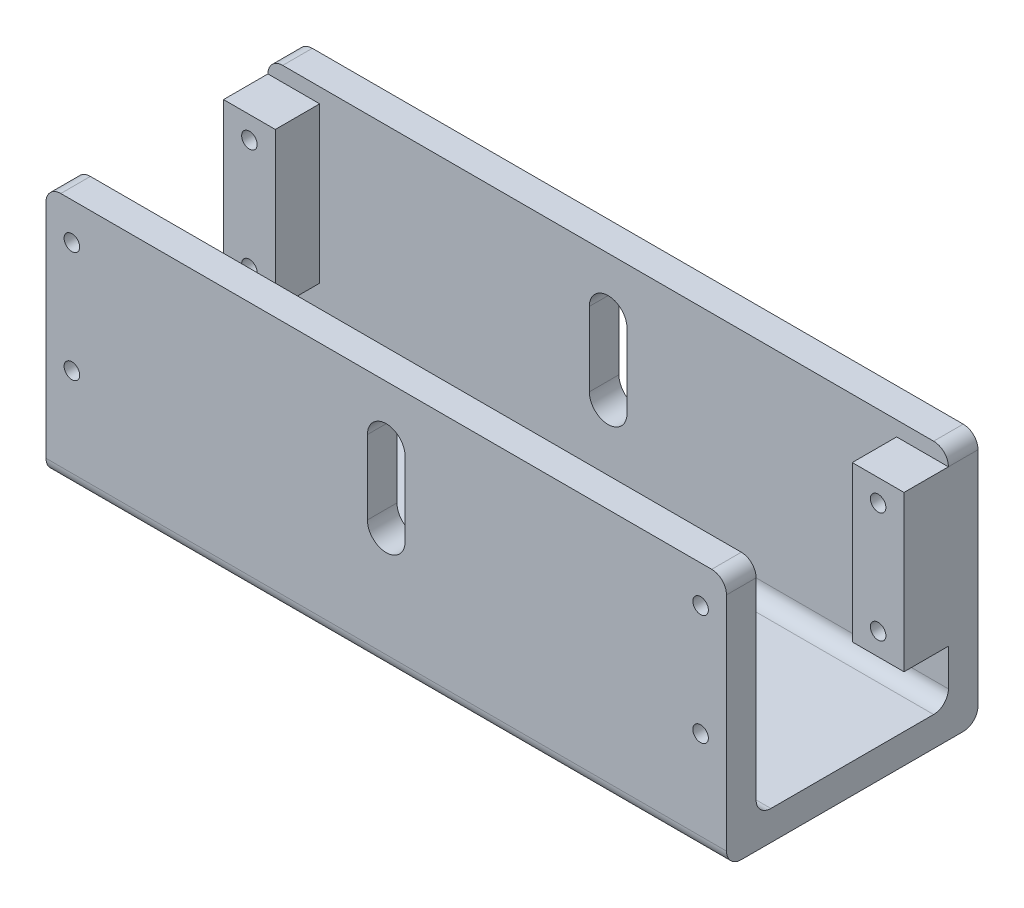
SolidWorks part; units mm, degrees
ref_plane "前视基准面" through (0, 0, 0) normal (0, 0, 1) x (1, 0, 0)
ref_plane "上视基准面" through (0, 0, 0) normal (0, 1, 0) x (1, 0, 0)
ref_plane "右视基准面" through (0, 0, 0) normal (1, 0, 0) x (0, 0, -1)
sketch "草图1" plane through (0, 0, 0) normal (0, 0, 1) x (1, 0, 0)
  line L1 (0, 0) -> (92, 0)
  line L2 (0, 0) -> (0, -30)
  line L3 (0, -30) -> (92, -30)
  line L4 (92, 0) -> (92, -30)
  line L5 (43.45, -17.5) -> (43.45, -7.5)
  line L6 (48.55, -17.5) -> (48.55, -7.5)
  circle A0 centre (3.5, -5) radius 1.05
  circle A1 centre (3.5, -20) radius 1.05
  circle A2 centre (88.5, -5) radius 1.05
  circle A3 centre (88.5, -20) radius 1.05
  arc A7 (43.45, -17.5) -> (48.55, -17.5) centre (46, -17.5) ccw
  arc A8 (48.55, -7.5) -> (43.45, -7.5) centre (46, -7.5) ccw
  point P17 (46.1066, -12.5)
  point P22 (46, 0)
  dimension "D3" = 2
  dimension "D5" = 7.5
  dimension "D6" = 5
  dimension "D1" = 92
  dimension "D2" = 30
  dimension "D7" = 43.45
  dimension "D8" = 5.1
  dimension "D4" = 2
extrude "凸台-拉伸1" add sketch "草图1" along normal blind 4
sketch "草图4" plane through (0, -30, 0) normal (0, -1, 0) x (-1, 0, 0)
  line L1 (0, 0) -> (-92, 0)
  line L2 (0, 0) -> (0, -30)
  line L3 (0, -30) -> (-92, -30)
  line L4 (-92, 0) -> (-92, -30)
  dimension "D1" = 92
  dimension "D2" = 30
extrude "凸台-拉伸4" add sketch "草图4" along normal blind 4
sketch "草图5" plane through (0, 0, 30) normal (0, 0, 1) x (1, 0, 0)
  line L1 (0, -34) -> (92, -34)
  line L2 (0, -34) -> (0, 0)
  line L3 (0, 0) -> (92, 0)
  line L4 (92, -34) -> (92, 0)
  circle A0 centre (3.5, -5) radius 1.05
  circle A1 centre (3.5, -20) radius 1.05
  circle A2 centre (88.5, -20) radius 1.05
  circle A3 centre (88.5, -5) radius 1.05
extrude "凸台-拉伸5" add sketch "草图5" along normal blind 4
fillet "圆角4" radius 2 8 edges at (46, -30, 30) (0, 0, 32) (92, 0, 32) (92, 0, 2) (0, 0, 2) (46, -34, 0) (46, -34, 34) (46, -30, 4)
sketch "草图7" plane through (0, 0, 0) normal (0, 0, -1) x (-1, 0, 0)
  line L0 (-46, -17.5) -> (-46, -7.5) construction
  line L1 (-48.55, -17.5) -> (-48.55, -7.5)
  line L2 (-43.45, -17.5) -> (-43.45, -7.5)
  arc A0 (-48.55, -17.5) -> (-43.45, -17.5) centre (-46, -17.5) ccw
  arc A1 (-43.45, -7.5) -> (-48.55, -7.5) centre (-46, -7.5) ccw
  point P4 (-46, -12.5)
extrude "切除-拉伸1" cut sketch "草图7" against normal blind 45
sketch "草图8" plane through (0, -34, 0) normal (0, -1, 0) x (-1, 0, 0)
  line L0 (-92, 0) -> (0, 0) construction
  line L1 (0, -32) -> (0, -2) construction
  circle A2 centre (-46, -16.5) radius 2.55
  dimension "D1" = 16.5
  dimension "D2" = 46
extrude "切除-拉伸2" cut sketch "草图8" against normal blind 5
sketch "草图9" plane through (0, 0, 4) normal (0, 0, 1) x (1, 0, 0)
  line L0 (92, -2) -> (92, -23)
  line L1 (0, -2) -> (7, -2)
  line L2 (0, -2) -> (0, -23)
  line L3 (0, -23) -> (7, -23)
  line L4 (7, -2) -> (7, -23)
  line L5 (85, -2) -> (92, -2)
  line L6 (85, -2) -> (85, -23)
  line L7 (85, -23) -> (92, -23)
  circle A1 centre (3.5, -5) radius 1.05 construction
  circle A3 centre (3.5, -5) radius 1.05
  circle A4 centre (3.5, -20) radius 1.05
  circle A5 centre (88.5, -5) radius 1.05
  circle A6 centre (88.5, -20) radius 1.05
  dimension "D2" = 3.5
  dimension "D3" = 2
  dimension "D1" = 21
extrude "凸台-拉伸6" add sketch "草图9" along normal blind 6
